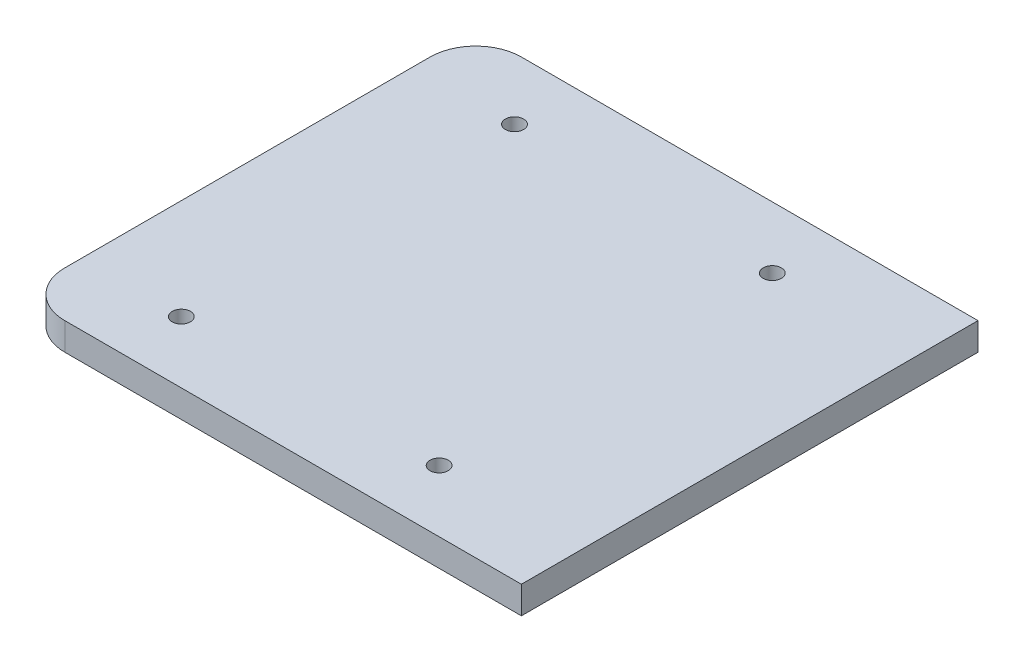
SolidWorks part; units mm, degrees
material "Acrylic (Medium-high impact)"
ref_plane "Front" through (0, 0, 0) normal (0, 0, 1) x (1, 0, 0)
ref_plane "Top" through (0, 0, 0) normal (0, 1, 0) x (1, 0, 0)
ref_plane "Right" through (0, 0, 0) normal (1, 0, 0) x (0, 0, -1)
sketch "Sketch1" plane through (0, 0, 0) normal (0, 1, 0) x (1, 0, 0)
  line L0 (50, 50) -> (60, 50)
  line L1 (50, -50) -> (-50, -50)
  line L2 (60, 50) -> (60, -50)
  line L3 (50, 50) -> (-50, 50)
  line L4 (-50, -50) -> (-50, 50)
  line L5 (60, -50) -> (50, -50)
  point P0 (0, 0)
  dimension "D1" = 100
  dimension "D2" = 100
  dimension "D3" = 10
extrude "Boss-Extrude1" add sketch "Sketch1" along normal blind 6
fillet "Fillet1" radius 10 2 edges at (-50, 3, -50) (-50, 3, 50)
sketch "Sketch3" plane through (0, 0, 0) normal (0, -1, 0) x (1, 0, 0)
  point P0 (-28, 36.4831)
  point P1 (28.4631, 36.4831)
  point P3 (-28, -36.4831)
  point P5 (28.4631, -36.4831)
hole_wizard "Ø4.0mm Dowel Hole1" positions "Sketch5" profile "Sketch6" hole size "Ø4.0" standard "ANSI Metric"
sketch "Sketch5" plane through (0, 6, 0) normal (0, 1, 0) x (1, 0, 0)
  point P0 (-28, 36.4831)
  point P3 (28.4631, 36.4831)
  point P6 (-28, -36.4831)
  point P9 (28.4631, -36.4831)
sketch "Sketch6" plane through (-28, 6, -36.4831) normal (1, 0, 0) x (0, 0, 1)
  line L0 (0, 0) -> (0, 99.5117)
  line L1 (0, 99.5117) -> (2, 98.31)
  line L2 (2, 98.31) -> (2, 0)
  line L5 (2, 0) -> (0, 0)
  line L10 (0, 99.5117) -> (-2, 98.31) construction
  line L11 (0, -6.35) -> (0, 107.95) construction
  dimension "Hole Dia." = 4
  dimension "Hole Depth" = 98.31
  dimension "Drill Angle" = 118
